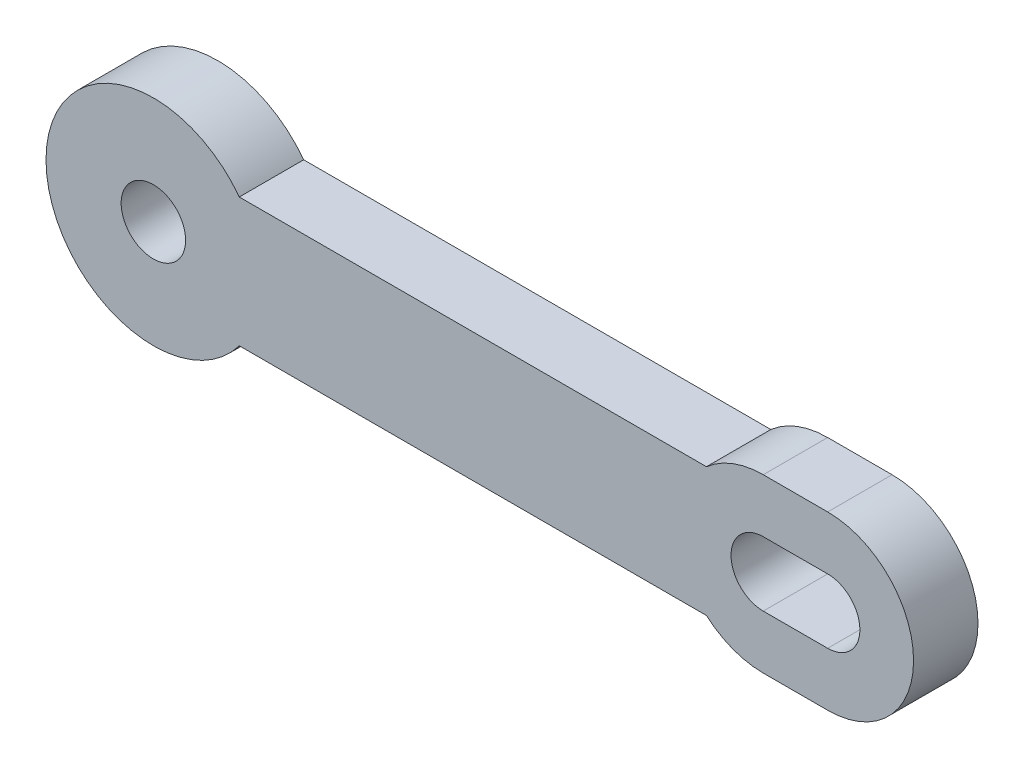
SolidWorks part; units mm, degrees
material "ABS"
ref_plane "Alzado" through (0, 0, 0) normal (0, 0, 1) x (1, 0, 0)
ref_plane "Planta" through (0, 0, 0) normal (0, 1, 0) x (1, 0, 0)
ref_plane "Vista lateral" through (0, 0, 0) normal (1, 0, 0) x (0, 0, -1)
sketch "Croquis1" plane through (0, 0, 0) normal (0, 0, 1) x (1, 0, 0)
  line L1 (0, -3) -> (25.7542, -3)
  line L2 (0, -3) -> (0, 3)
  line L3 (0, 3) -> (25.7542, 3)
  line L4 (28.4, -1.5) -> (28.4, 1.5)
  line L5 (28.4, -1.5) -> (31.4, -1.5)
  line L6 (28.4, -1.5) -> (28.4, 1.5)
  line L8 (28.4, -1.5) -> (28.4, 0.5)
  line L11 (28.4, 1.5) -> (31.4, 1.5)
  line L12 (31.4, -1.5) -> (31.4, 1.5)
  line L13 (28.4, -4) -> (31.4, -4)
  line L15 (28.4, 4) -> (31.4, 4)
  line L17 (31.4, -1.5) -> (31.4, 1.5)
  line L18 (28.4, -1.5) -> (28.4, 1.5)
  circle A0 centre (0, 0) radius 1.5
  circle A1 centre (0, 0) radius 5
  circle A2 centre (28.4, 0) radius 1.5
  arc A8 (28.4, 4) -> (28.4, -4) centre (28.4, 0) ccw
  circle A9 centre (31.4, 0) radius 1.5
  arc A11 (31.4, -4) -> (31.4, 4) centre (31.4, 0) ccw
  point P13 (0, 0)
  point P15 (28.4, 0)
  dimension "D1" = 10
  dimension "D2" = 3
  dimension "D3" = 3
  dimension "D4" = 8
  dimension "D9" = 3
  dimension "D5" = 3
  dimension "D6" = 6
  dimension "D7" = 28.4
extrude "Saliente-Extruir2" add sketch "Croquis1" along normal blind 3 contours L3 A1 L1 L2 A0 | L1 A1 L3 L2 A0 | A8 L3 A1 L1 | L13 A11 L15 A8 A9 L5 A2 L11
